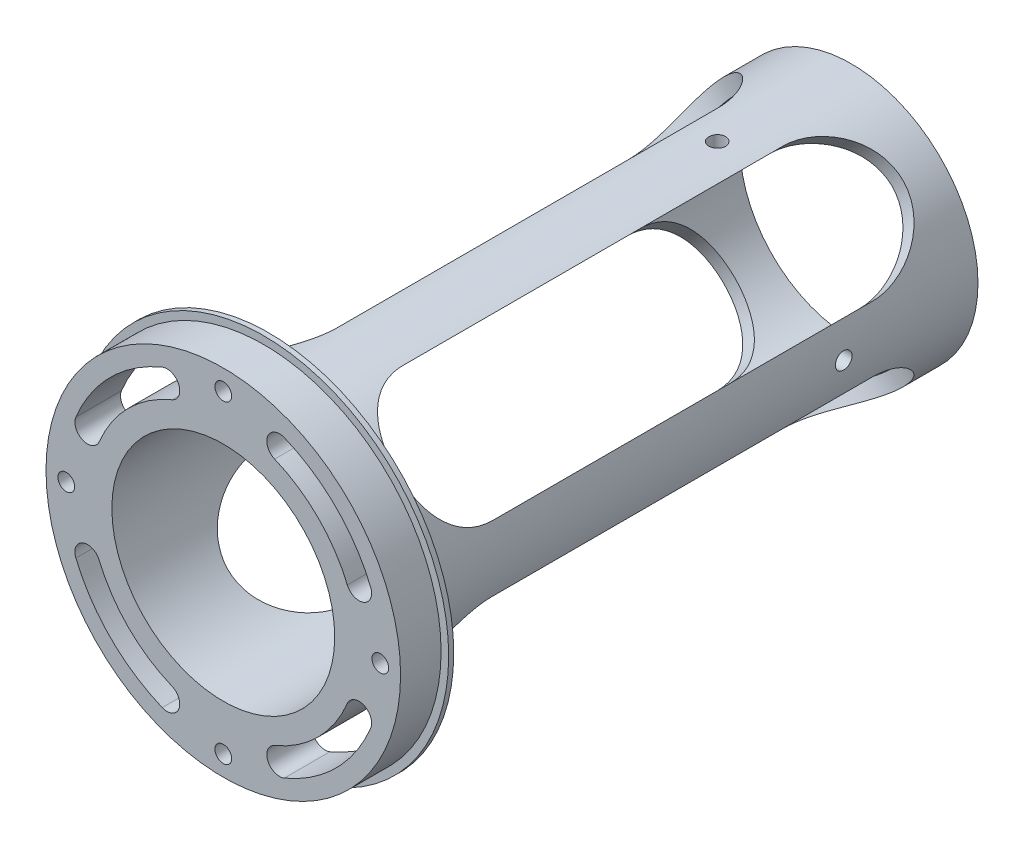
SolidWorks part; units mm, degrees
material "6061 合金"
ref_plane "前视基准面" through (0, 0, 0) normal (0, 0, 1) x (1, 0, 0)
ref_plane "上视基准面" through (0, 0, 0) normal (0, 1, 0) x (1, 0, 0)
ref_plane "右视基准面" through (0, 0, 0) normal (1, 0, 0) x (0, 0, -1)
sketch "草图1" plane through (0, 0, 0) normal (0, 1, 0) x (1, 0, 0)
  line L1 (36.5, 0) -> (36.5, 1)
  line L2 (36.5, 1) -> (25, 1)
  line L3 (25, 1) -> (25, 116)
  line L4 (25, 116) -> (22, 116)
  line L5 (22, 116) -> (22, 0)
  line L6 (0, 0) -> (0, 11.7715) construction
  line L8 (22, 0) -> (36.5, 0)
  dimension "D1" = 44
  dimension "D2" = 50
  dimension "D3" = 1
  dimension "D4" = 73
  dimension "D5" = 115
revolve "旋转1" add sketch "草图1" angle 360 about L6
sketch "草图5" plane through (0, 0, 0) normal (0, 0, 1) x (1, 0, 0)
  circle A0 centre (0, 0) radius 35
  circle A25 centre (0, 0) radius 22 construction
  circle A26 centre (0, 0) radius 22
  dimension "D1" = 70
extrude "凸台-拉伸1" add sketch "草图5" along normal blind 8
hole_wizard "M4 螺纹孔3" positions "草图3" profile "草图4" tap size "M4" standard "GB" end condition through all
sketch "草图3" plane through (0, 0, 8) normal (0, 0, -1) x (-1, 0, 0)
  circle A0 centre (0, 0) radius 31 construction
  point P0 (31, 0)
  point P10 (0, -31)
  point P11 (-31, 0)
  point P12 (0, 31)
  dimension "D1" = 4
  dimension "D2" = 62
sketch "草图4" plane through (-31, 0, 8) normal (1, 0, 0) x (0, -1, 0)
  line L0 (0, 0) -> (0, 124)
  line L1 (0, 124) -> (1.65, 124)
  line L2 (1.65, 124) -> (1.65, 0)
  line L5 (1.65, 0) -> (0, 0)
  line L11 (0, -6.35) -> (0, 107.95) construction
  dimension "通孔螺纹孔钻头直径" = 3.3
  dimension "通孔螺纹孔钻头深度" = 124
cosmetic thread "孔螺蚊线14" parameters "D2"=4
cosmetic thread "孔螺蚊线15" parameters "D2"=4
cosmetic thread "孔螺蚊线16" parameters "D2"=4
cosmetic thread "孔螺蚊线17" parameters "D2"=4
hole_wizard "M4 螺纹孔2" positions "草图8" profile "草图9" tap size "M4" standard "GB"
sketch "草图8" plane through (0, 0, 0) normal (0, 1, 0) x (1, 0, 0)
  line L0 (36.5, 1) -> (-36.5, 1) construction
  point P0 (0, 89.5)
  dimension "D1" = 88.5
sketch "草图9" plane through (0, 0, -89.5) normal (1, 0, 0) x (0, 0, -1)
  line L0 (0, 0) -> (0, 36.5)
  line L1 (0, 36.5) -> (1.65, 36.5)
  line L2 (1.65, 36.5) -> (1.65, 0)
  line L5 (1.65, 0) -> (0, 0)
  line L11 (0, -6.35) -> (0, 107.95) construction
  dimension "通孔螺纹孔钻头直径" = 3.3
  dimension "通孔螺纹孔钻头深度" = 36.5
cosmetic thread "孔螺蚊线5" parameters "D2"=4
sketch "草图2" plane through (0, 0, -1) normal (0, 0, -1) x (-1, 0, 0)
  arc A5 (-26.7925, 11.0978) -> (-11.0978, 26.7925) centre (0, 0) cw construction
  arc A6 (-12.0545, 29.1022) -> (-29.1022, 12.0545) centre (0, 0) ccw
  arc A7 (-10.1411, 24.4828) -> (-24.4828, 10.1411) centre (0, 0) ccw
  arc A8 (-10.1411, 24.4828) -> (-12.0545, 29.1022) centre (-11.0978, 26.7925) ccw
  arc A9 (-29.1022, 12.0545) -> (-24.4828, 10.1411) centre (-26.7925, 11.0978) ccw
  arc A15 (11.0978, 26.7925) -> (26.7925, 11.0978) centre (0, 0) cw construction
  arc A42 (29.1022, 12.0545) -> (12.0545, 29.1022) centre (0, 0) ccw
  arc A43 (24.4828, 10.1411) -> (10.1411, 24.4828) centre (0, 0) ccw
  arc A44 (24.4828, 10.1411) -> (29.1022, 12.0545) centre (26.7925, 11.0978) ccw
  arc A45 (12.0545, 29.1022) -> (10.1411, 24.4828) centre (11.0978, 26.7925) ccw
  arc A46 (26.7925, -11.0978) -> (11.0978, -26.7925) centre (0, 0) cw construction
  arc A47 (12.0545, -29.1022) -> (29.1022, -12.0545) centre (0, 0) ccw
  arc A48 (10.1411, -24.4828) -> (24.4828, -10.1411) centre (0, 0) ccw
  arc A49 (10.1411, -24.4828) -> (12.0545, -29.1022) centre (11.0978, -26.7925) ccw
  arc A50 (29.1022, -12.0545) -> (24.4828, -10.1411) centre (26.7925, -11.0978) ccw
  arc A51 (-11.0978, -26.7925) -> (-26.7925, -11.0978) centre (0, 0) cw construction
  arc A52 (-29.1022, -12.0545) -> (-12.0545, -29.1022) centre (0, 0) ccw
  arc A53 (-24.4828, -10.1411) -> (-10.1411, -24.4828) centre (0, 0) ccw
  arc A54 (-24.4828, -10.1411) -> (-29.1022, -12.0545) centre (-26.7925, -11.0978) ccw
  arc A55 (-12.0545, -29.1022) -> (-10.1411, -24.4828) centre (-11.0978, -26.7925) ccw
  point P13 (-20.5061, 20.5061)
  point P18 (20.5061, 20.5061)
  point P27 (20.5061, -20.5061)
  point P36 (-20.5061, -20.5061)
  dimension "D3" = 26.5
  dimension "D4" = 2.5
  dimension "D5" = 45
  dimension "D6" = 4
extrude "切除-拉伸1" cut sketch "草图2" against normal through all
ref_plane "基准面1" through (0, 0, 0) normal (0.7071, 0.7071, 0) x (0, 0, -1)
sketch "草图10" plane through (0, 0, 0) normal (0.7071, 0.7071, 0) x (0, 0, -1)
  line L0 (21, 0) -> (96, 0) construction
  line L1 (21, 12.5) -> (96, 12.5)
  line L2 (21, -12.5) -> (96, -12.5)
  line L3 (1, -25) -> (1, 25) construction
  arc A0 (21, 12.5) -> (21, -12.5) centre (21, 0) ccw
  arc A1 (96, -12.5) -> (96, 12.5) centre (96, 0) ccw
  point P3 (58.5, 0)
  point P8 (8.5, 0)
  point P9 (108.5, 0)
  dimension "D1" = 100
  dimension "D2" = 7.5
  dimension "D3" = 25
extrude "切除-拉伸2" cut sketch "草图10" along normal through all
pattern_circular "阵列(圆周)1" count 4 over 360 about axis through (0, 0, 0) along (0, 0, 1) of "M4 螺纹孔2", "切除-拉伸2"
